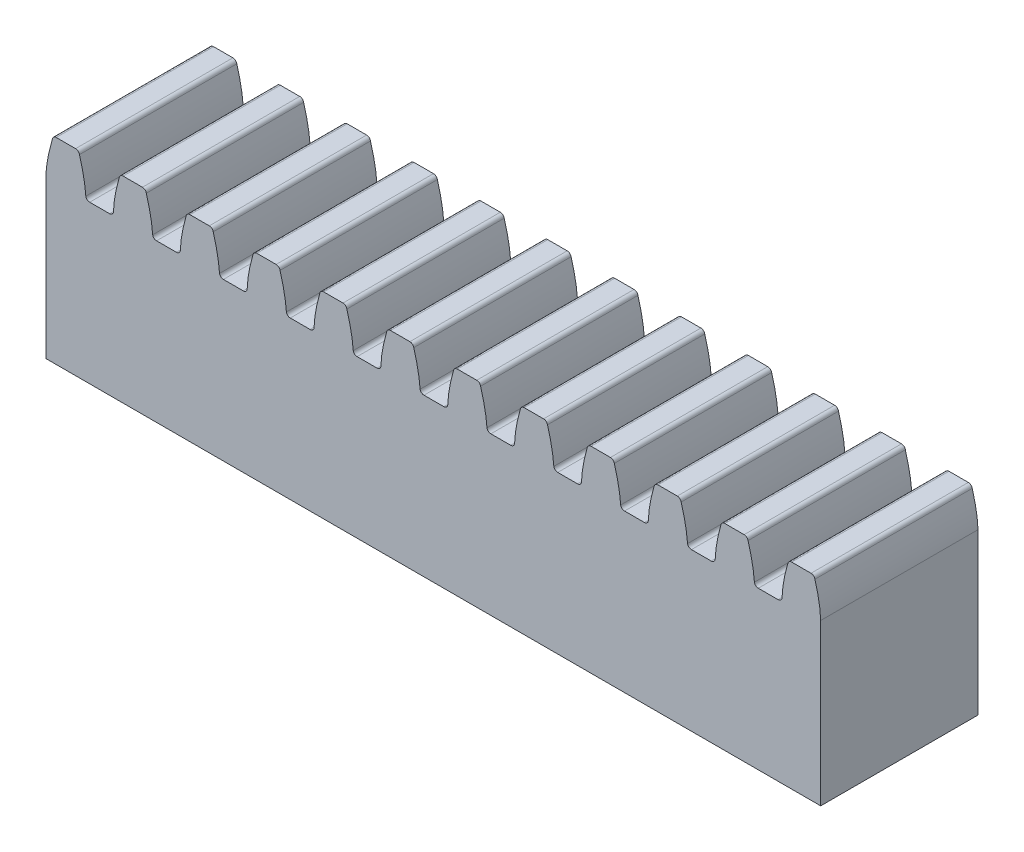
SolidWorks part; units mm, degrees
ref_plane "Front Plane" through (0, 0, 0) normal (0, 0, 1) x (1, 0, 0)
ref_plane "Top Plane" through (0, 0, 0) normal (0, 1, 0) x (1, 0, 0)
ref_plane "Right Plane" through (0, 0, 0) normal (1, 0, 0) x (0, 0, -1)
sketch "Sketch2" plane through (0, 0, 0) normal (0, 0, 1) x (1, 0, 0)
  line L0 (2.5316, 5) -> (2.5316, -0.7164) construction
  line L1 (5.5557, 0) -> (8.0805, 0)
  line L2 (0, 0) -> (0, -20)
  line L3 (0, -20) -> (98.4904, -20)
  line L4 (90.5557, 0) -> (93.0805, 0)
  line L5 (1.3012, 5) -> (3.7621, 5)
  line L6 (9.8012, 5) -> (12.2621, 5)
  line L7 (4.1816, -1.5081) -> (4.1816, 5) construction
  line L8 (98.4904, 0.4132) -> (98.4904, -20)
  line L9 (82.0557, 0) -> (84.5805, 0)
  line L10 (73.5557, 0) -> (76.0805, 0)
  line L11 (18.3012, 5) -> (20.7621, 5)
  line L12 (26.8012, 5) -> (29.2621, 5)
  line L13 (35.3012, 5) -> (37.7621, 5)
  line L14 (43.8012, 5) -> (46.2621, 5)
  line L15 (52.3012, 5) -> (54.7621, 5)
  line L16 (60.8012, 5) -> (63.2621, 5)
  line L17 (69.3012, 5) -> (71.7621, 5)
  line L18 (77.8012, 5) -> (80.2621, 5)
  line L19 (86.3012, 5) -> (88.7621, 5)
  line L20 (94.8012, 5) -> (97.2621, 5)
  line L21 (65.0557, 0) -> (67.5805, 0)
  line L22 (56.5557, 0) -> (59.0805, 0)
  line L23 (48.0557, 0) -> (50.5805, 0)
  line L24 (39.5557, 0) -> (42.0805, 0)
  line L25 (31.0557, 0) -> (33.5805, 0)
  line L26 (22.5557, 0) -> (25.0805, 0)
  line L27 (14.0557, 0) -> (16.5805, 0)
  line L28 (0, 0.4132) -> (0, 0)
  arc A0 (5.0633, 0.4132) -> (5.5557, 0) centre (5.5557, 0.5) ccw
  arc A2 (3.7621, 5) -> (4.2545, 4.5868) centre (3.7621, 4.5) cw
  arc A3 (0.8088, 4.5868) -> (1.3012, 5) centre (1.3012, 4.5) cw
  arc A4 (9.3088, 4.5868) -> (9.8012, 5) centre (9.8012, 4.5) cw
  arc A5 (12.2621, 5) -> (12.7545, 4.5868) centre (12.2621, 4.5) cw
  arc A6 (13.5633, 0.4132) -> (14.0557, 0) centre (14.0557, 0.5) ccw
  arc A7 (8.0805, 0) -> (8.5729, 0.4132) centre (8.0805, 0.5) ccw
  arc A8 (17.8088, 4.5868) -> (18.3012, 5) centre (18.3012, 4.5) cw
  arc A9 (20.7621, 5) -> (21.2545, 4.5868) centre (20.7621, 4.5) cw
  arc A10 (22.0633, 0.4132) -> (22.5557, 0) centre (22.5557, 0.5) ccw
  arc A11 (16.5805, 0) -> (17.0729, 0.4132) centre (16.5805, 0.5) ccw
  arc A12 (26.3088, 4.5868) -> (26.8012, 5) centre (26.8012, 4.5) cw
  arc A13 (29.2621, 5) -> (29.7545, 4.5868) centre (29.2621, 4.5) cw
  arc A14 (30.5633, 0.4132) -> (31.0557, 0) centre (31.0557, 0.5) ccw
  arc A15 (25.0805, 0) -> (25.5729, 0.4132) centre (25.0805, 0.5) ccw
  arc A16 (34.8088, 4.5868) -> (35.3012, 5) centre (35.3012, 4.5) cw
  arc A17 (37.7621, 5) -> (38.2545, 4.5868) centre (37.7621, 4.5) cw
  arc A18 (39.0633, 0.4132) -> (39.5557, 0) centre (39.5557, 0.5) ccw
  arc A19 (33.5805, 0) -> (34.0729, 0.4132) centre (33.5805, 0.5) ccw
  arc A20 (43.3088, 4.5868) -> (43.8012, 5) centre (43.8012, 4.5) cw
  arc A21 (46.2621, 5) -> (46.7545, 4.5868) centre (46.2621, 4.5) cw
  arc A22 (47.5633, 0.4132) -> (48.0557, 0) centre (48.0557, 0.5) ccw
  arc A23 (42.0805, 0) -> (42.5729, 0.4132) centre (42.0805, 0.5) ccw
  arc A24 (51.8088, 4.5868) -> (52.3012, 5) centre (52.3012, 4.5) cw
  arc A25 (54.7621, 5) -> (55.2545, 4.5868) centre (54.7621, 4.5) cw
  arc A26 (56.0633, 0.4132) -> (56.5557, 0) centre (56.5557, 0.5) ccw
  arc A27 (50.5805, 0) -> (51.0729, 0.4132) centre (50.5805, 0.5) ccw
  arc A28 (60.3088, 4.5868) -> (60.8012, 5) centre (60.8012, 4.5) cw
  arc A29 (63.2621, 5) -> (63.7545, 4.5868) centre (63.2621, 4.5) cw
  arc A30 (64.5633, 0.4132) -> (65.0557, 0) centre (65.0557, 0.5) ccw
  arc A31 (59.0805, 0) -> (59.5729, 0.4132) centre (59.0805, 0.5) ccw
  arc A32 (68.8088, 4.5868) -> (69.3012, 5) centre (69.3012, 4.5) cw
  arc A33 (71.7621, 5) -> (72.2545, 4.5868) centre (71.7621, 4.5) cw
  arc A34 (73.0633, 0.4132) -> (73.5557, 0) centre (73.5557, 0.5) ccw
  arc A35 (67.5805, 0) -> (68.0729, 0.4132) centre (67.5805, 0.5) ccw
  arc A36 (77.3088, 4.5868) -> (77.8012, 5) centre (77.8012, 4.5) cw
  arc A37 (80.2621, 5) -> (80.7545, 4.5868) centre (80.2621, 4.5) cw
  arc A38 (81.5633, 0.4132) -> (82.0557, 0) centre (82.0557, 0.5) ccw
  arc A39 (76.0805, 0) -> (76.5729, 0.4132) centre (76.0805, 0.5) ccw
  arc A40 (85.8088, 4.5868) -> (86.3012, 5) centre (86.3012, 4.5) cw
  arc A41 (88.7621, 5) -> (89.2545, 4.5868) centre (88.7621, 4.5) cw
  arc A42 (90.0633, 0.4132) -> (90.5557, 0) centre (90.5557, 0.5) ccw
  arc A43 (84.5805, 0) -> (85.0729, 0.4132) centre (84.5805, 0.5) ccw
  arc A44 (94.3088, 4.5868) -> (94.8012, 5) centre (94.8012, 4.5) cw
  arc A45 (97.2621, 5) -> (97.7545, 4.5868) centre (97.2621, 4.5) cw
  arc A47 (93.0805, 0) -> (93.5729, 0.4132) centre (93.0805, 0.5) ccw
  arc A48 (98.5633, 0.4132) -> (99.0557, 0) centre (99.0557, 0.5) ccw [skipped]
  spline S0 degree 2 poles (0.8088, 4.5868) (0.137, 2.2865) (0, 0.4132) knots 0 0 0 1 1 1
  spline S1 degree 2 poles (4.2545, 4.5868) (4.9263, 2.2865) (5.0633, 0.4132) knots 0 0 0 1 1 1
  spline S2 degree 2 poles (9.3088, 4.5868) (8.637, 2.2865) (8.5729, 0.4132) knots 0 0 0 1 1 1
  spline S3 degree 2 poles (12.7545, 4.5868) (13.4263, 2.2865) (13.5633, 0.4132) knots 0 0 0 1 1 1
  spline S4 degree 2 poles (17.8088, 4.5868) (17.137, 2.2865) (17.0729, 0.4132) knots 0 0 0 1 1 1
  spline S5 degree 2 poles (21.2545, 4.5868) (21.9263, 2.2865) (22.0633, 0.4132) knots 0 0 0 1 1 1
  spline S6 degree 2 poles (26.3088, 4.5868) (25.637, 2.2865) (25.5729, 0.4132) knots 0 0 0 1 1 1
  spline S7 degree 2 poles (29.7545, 4.5868) (30.4263, 2.2865) (30.5633, 0.4132) knots 0 0 0 1 1 1
  spline S8 degree 2 poles (34.8088, 4.5868) (34.137, 2.2865) (34.0729, 0.4132) knots 0 0 0 1 1 1
  spline S9 degree 2 poles (38.2545, 4.5868) (38.9263, 2.2865) (39.0633, 0.4132) knots 0 0 0 1 1 1
  spline S10 degree 2 poles (43.3088, 4.5868) (42.637, 2.2865) (42.5729, 0.4132) knots 0 0 0 1 1 1
  spline S11 degree 2 poles (46.7545, 4.5868) (47.4263, 2.2865) (47.5633, 0.4132) knots 0 0 0 1 1 1
  spline S12 degree 2 poles (51.8088, 4.5868) (51.137, 2.2865) (51.0729, 0.4132) knots 0 0 0 1 1 1
  spline S13 degree 2 poles (55.2545, 4.5868) (55.9263, 2.2865) (56.0633, 0.4132) knots 0 0 0 1 1 1
  spline S14 degree 2 poles (60.3088, 4.5868) (59.637, 2.2865) (59.5729, 0.4132) knots 0 0 0 1 1 1
  spline S15 degree 2 poles (63.7545, 4.5868) (64.4263, 2.2865) (64.5633, 0.4132) knots 0 0 0 1 1 1
  spline S16 degree 2 poles (68.8088, 4.5868) (68.137, 2.2865) (68.0729, 0.4132) knots 0 0 0 1 1 1
  spline S17 degree 2 poles (72.2545, 4.5868) (72.9263, 2.2865) (73.0633, 0.4132) knots 0 0 0 1 1 1
  spline S18 degree 2 poles (77.3088, 4.5868) (76.637, 2.2865) (76.5729, 0.4132) knots 0 0 0 1 1 1
  spline S19 degree 2 poles (80.7545, 4.5868) (81.4263, 2.2865) (81.5633, 0.4132) knots 0 0 0 1 1 1
  spline S20 degree 2 poles (85.8088, 4.5868) (85.137, 2.2865) (85.0729, 0.4132) knots 0 0 0 1 1 1
  spline S21 degree 2 poles (89.2545, 4.5868) (89.9263, 2.2865) (90.0633, 0.4132) knots 0 0 0 1 1 1
  spline S22 degree 2 poles (94.3088, 4.5868) (93.637, 2.2865) (93.5729, 0.4132) knots 0 0 0 1 1 1
  spline S23 degree 2 poles (97.7545, 4.5868) (98.4263, 2.2865) (98.4904, 0.4132) knots 0 0 0 1 1 1
  point P22 (0.8816, 5)
  dimension "D1" = 0.5
  dimension "D3" = 12
  dimension "D4" = 3.3
  dimension "D5" = 5
extrude "Boss-Extrude1" add sketch "Sketch2" along normal blind 20
